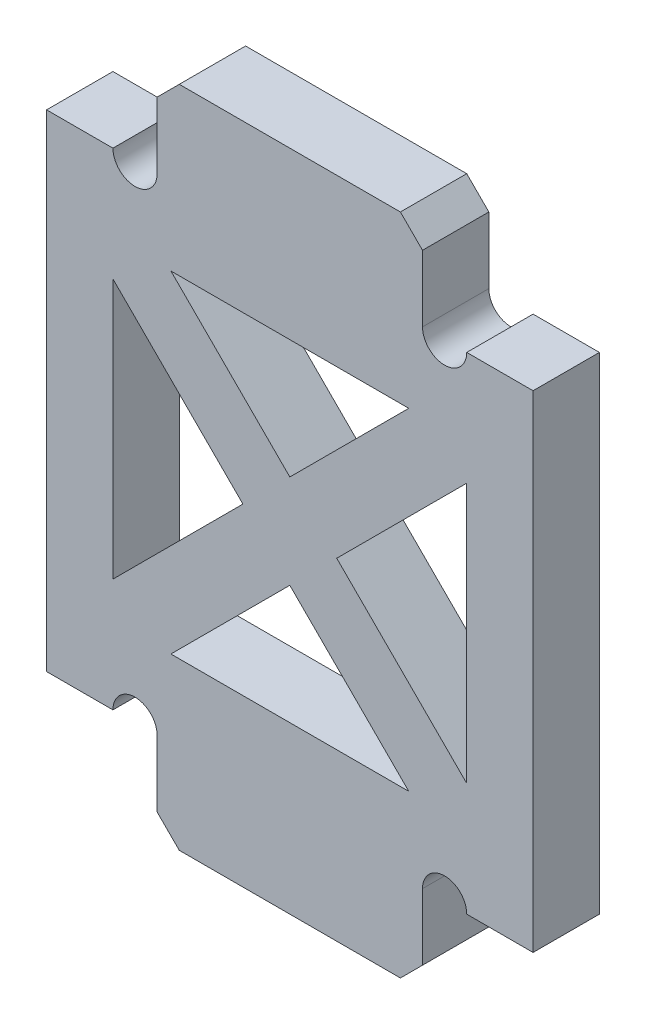
SolidWorks part; units mm, degrees
material "碳板"
ref_plane "前视基准面" through (0, 0, 0) normal (0, 0, 1) x (1, 0, 0)
ref_plane "上视基准面" through (0, 0, 0) normal (0, 1, 0) x (1, 0, 0)
ref_plane "右视基准面" through (0, 0, 0) normal (1, 0, 0) x (0, 0, -1)
sketch "草图1" plane through (0, 0, 0) normal (0, 0, 1) x (1, 0, 0)
  line L0 (0, 19.9183) -> (0, -17.9901) construction
  line L1 (-11, 11) -> (11, 11)
  line L2 (-11, 11) -> (-11, -11)
  line L3 (-11, -11) -> (11, -11)
  line L4 (11, 11) -> (11, -11)
  line L5 (-11, 11) -> (11, -11) construction
  line L6 (-11, -11) -> (11, 11) construction
  line L7 (-22.5399, 0) -> (24.3637, 0) construction
  line L8 (-6, 11) -> (-6, 15)
  line L9 (-6, 15) -> (6, 15)
  line L10 (6, 11) -> (6, 15)
  line L11 (6, -11) -> (6, -15)
  line L12 (-6, -15) -> (6, -15)
  line L13 (-6, -11) -> (-6, -15)
  line L14 (5.3787, 7.5) -> (-5.3787, 7.5)
  line L15 (-5.3787, 7.5) -> (0, 2.1213)
  line L16 (-2.1213, 0) -> (-8, 5.8787)
  line L17 (-8, 5.8787) -> (-8, -5.8787)
  line L18 (5.3787, 7.5) -> (0, 2.1213)
  line L19 (2.1213, 0) -> (8, 5.8787)
  line L20 (8, 5.8787) -> (8, -5.8787)
  line L21 (2.1213, 0) -> (8, -5.8787)
  line L22 (5.3787, -7.5) -> (-5.3787, -7.5)
  line L23 (-5.3787, -7.5) -> (0, -2.1213)
  line L24 (5.3787, -7.5) -> (0, -2.1213)
  line L25 (-2.1213, 0) -> (-8, -5.8787)
  circle A0 centre (-7, 11) radius 1
  circle A1 centre (7, 11) radius 1
  circle A2 centre (7, -11) radius 1
  circle A3 centre (-7, -11) radius 1
  point P0 (0, 0)
  point P15 (0, 15)
  point P34 (0, 7.5)
  point P38 (8, 0)
  point P42 (-8, 0)
  dimension "D4" = 2
  dimension "D1" = 30
  dimension "D2" = 4
  dimension "D3" = 12
  dimension "D5" = 4
  dimension "D6" = 1.5
  dimension "D7" = 1.5
  dimension "D8" = 3
  dimension "D9" = 3.5
extrude "凸台-拉伸1" add sketch "草图1" along normal mid plane 3 contours L3 A3 A2 L4 L1 A1 A0 L2 L24 L22 L23 L21 L19 L20 L14 L18 L15 L16 L25 L17 | L1 L10 L9 L8 | L3 L13 L12 L11
chamfer "倒角1" distance 1 angle 45 4 edges at (6, -15, 0) (-6, -15, 0) (6, 15, 0) (-6, 15, 0)
